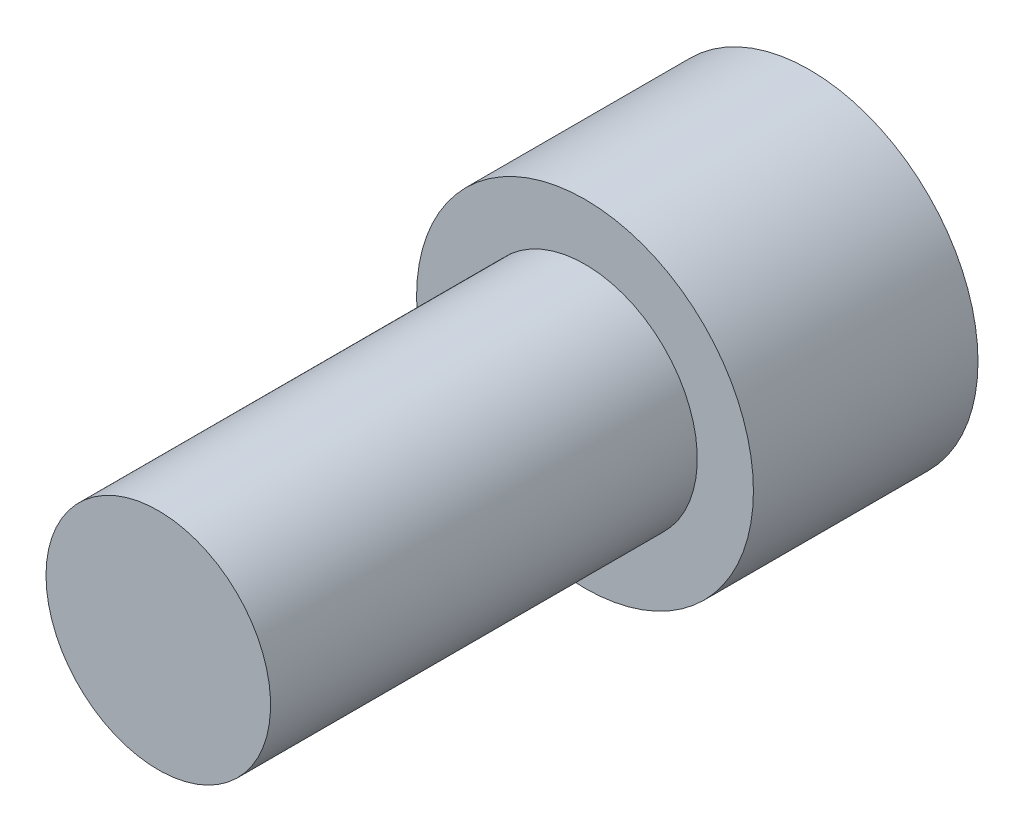
SolidWorks part; units mm, degrees
ref_plane "Ön Düzlem" through (0, 0, 0) normal (0, 0, 1) x (1, 0, 0)
ref_plane "Üst Düzlem" through (0, 0, 0) normal (0, 1, 0) x (1, 0, 0)
ref_plane "Sağ Düzlem" through (0, 0, 0) normal (1, 0, 0) x (0, 0, -1)
sketch "Sketch1" plane through (0, 0, 0) normal (0, 0, 1) x (1, 0, 0)
  circle A0 centre (0, 0) radius 7.5
  dimension "D1" = 15
extrude "Boss-Extrude1" add sketch "Sketch1" along normal blind 250
sketch "Sketch2" plane through (0, 0, 0) normal (0, 0, 1) x (1, 0, 0)
  circle A0 centre (0, 0) radius 5
  dimension "D1" = 10
extrude "Cut-Extrude1" cut sketch "Sketch2" along normal blind 10
ref_plane "Plane1" through (0, 0, 20) normal (0, 0, -1) x (-1, 0, 0)
sketch "Sketch3" plane through (0, 0, 10) normal (0, 0, -1) x (-1, 0, 0)
  circle A0 centre (0, 0) radius 5
  circle A1 centre (0, 0) radius 9.435
extrude "Cut-Extrude2" cut sketch "Sketch3" against normal blind 19
sketch "Sketch5" plane through (0, 0, 29) normal (0, 0, -1) x (-1, 0, 0)
  circle A0 centre (0, 0) radius 25.7657
extrude "Cut-Extrude3" cut sketch "Sketch5" against normal up to surface (221 mm away) up to face at (7.5, 0, 250)
sketch "Sketch6" plane through (0, 0, 10) normal (0, 0, -1) x (-1, 0, 0)
  circle A0 centre (0, 0) radius 5.5
  dimension "D1" = 11
extrude "Boss-Extrude2" add sketch "Sketch6" along normal blind 10
